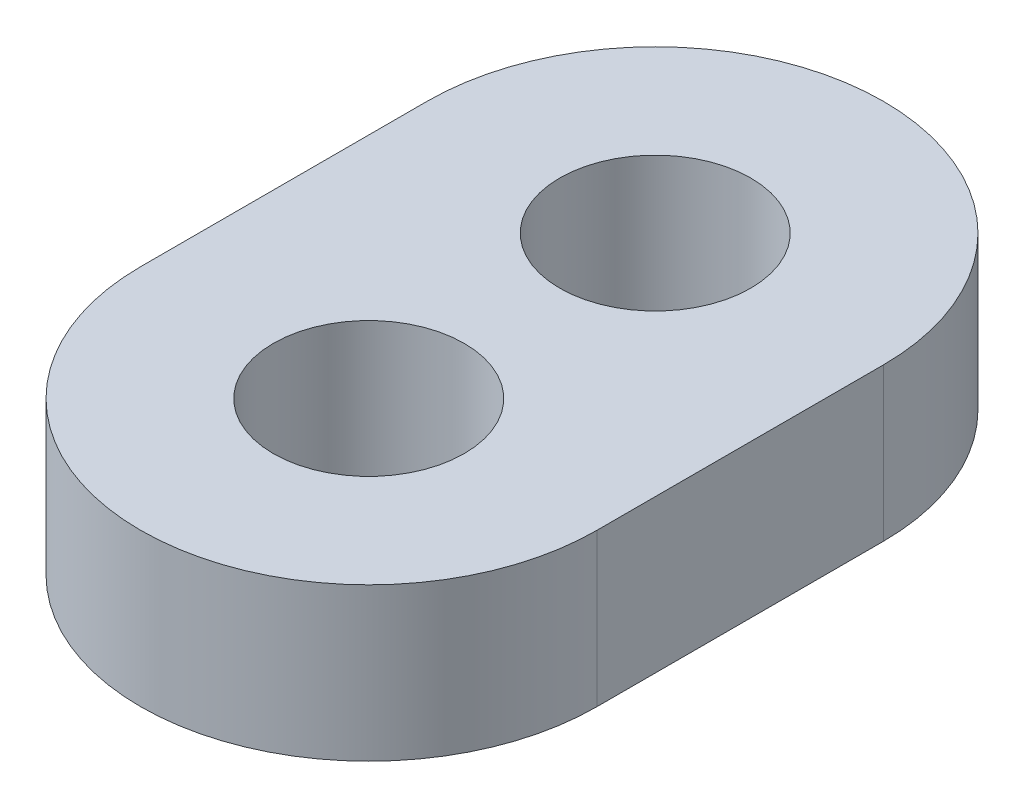
SolidWorks part; units mm, degrees
ref_plane "Ebene vorne" through (0, 0, 0) normal (0, 0, 1) x (1, 0, 0)
ref_plane "Ebene oben" through (0, 0, 0) normal (0, 1, 0) x (1, 0, 0)
ref_plane "Ebene rechts" through (0, 0, 0) normal (1, 0, 0) x (0, 0, -1)
sketch "Skizze16" plane through (0, -5, 0) normal (0, -1, 0) x (1, 0, 0)
  line L0 (0, -6.5) -> (0, -14) construction
  line L1 (5.9751, -6.5) -> (5.9751, -14)
  line L2 (-5.9751, -6.5) -> (-5.9751, -14)
  circle A0 centre (0, -14) radius 2.5
  circle A1 centre (0, -6.5) radius 2.5
  arc A2 (5.9751, -6.5) -> (-5.9751, -6.5) centre (0, -6.5) ccw
  arc A3 (-5.9751, -14) -> (5.9751, -14) centre (0, -14) ccw
  point P6 (0, -10.25)
extrude "Aufsatz-Linear austragen1" add sketch "Skizze16" along normal blind 4
